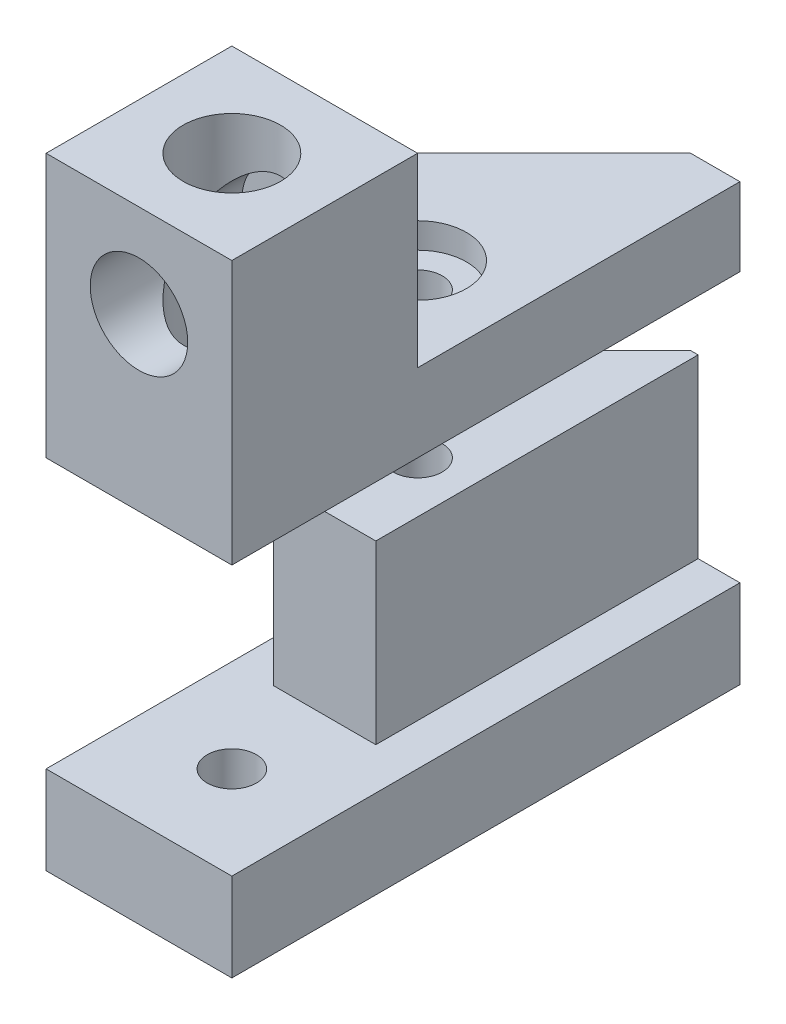
SolidWorks part; units mm, degrees
ref_plane "Front Plane" through (0, 0, 0) normal (0, 0, 1) x (1, 0, 0)
ref_plane "Top Plane" through (0, 0, 0) normal (0, 1, 0) x (1, 0, 0)
ref_plane "Right Plane" through (0, 0, 0) normal (1, 0, 0) x (0, 0, -1)
sketch "Sketch1" plane through (0, 0, 0) normal (0, 1, 0) x (1, 0, 0)
  line L1 (-10, 10) -> (10, 10) construction
  line L2 (-10, 10) -> (-10, -10) construction
  line L3 (-10, -10) -> (10, -10) construction
  line L4 (10, 10) -> (10, -10) construction
  line L5 (-10, 10) -> (10, -10) construction
  line L6 (-10, -10) -> (10, 10) construction
  line L7 (10, 10) -> (-10, 10) construction
  line L8 (10, 10) -> (10, 30) construction
  line L9 (10, 30) -> (-10, 30) construction
  line L10 (-10, 10) -> (-10, 30) construction
  circle A0 centre (0, 0) radius 2.5 construction
  circle A1 centre (0, 20) radius 2.5 construction
  circle A2 centre (0, 0) radius 6.5 construction
  circle A3 centre (0, 0) radius 7.5 construction
  circle A4 centre (0, 20) radius 2.5 construction
  circle A5 centre (0, 20) radius 7.5 construction
  circle A6 centre (0, 20) radius 6.5 construction
  point P0 (0, 0)
  point P6 (0, 0)
  point P10 (0, 20)
  dimension "D4" = 5
  dimension "D5" = 5
  dimension "D6" = 13
  dimension "D7" = 15
  dimension "D1" = 20
  dimension "D2" = 20
  dimension "D3" = 20
sketch "Sketch2" plane through (0, 0, 0) normal (0, 1, 0) x (1, 0, 0)
  line L1 (10, -10) -> (-10, -10)
  line L2 (10, -10) -> (10, 30)
  line L3 (10, 30) -> (-10, 30) construction
  line L4 (-10, -10) -> (-10, 30)
  line L5 (10, 44.7) -> (10, 30)
  line L6 (10, 30) -> (-10, 30) construction
  line L7 (-10, 30) -> (10, 30) construction
  line L9 (-10, 30) -> (10, 30) construction
  line L11 (10, 44.7) -> (4.7, 44.7)
  line L12 (-10, 30) -> (4.7, 44.7)
  line L13 (10.3961, 44.7) -> (10, 44.7) construction
  point P9 (0, 0)
  point P10 (9.6039, 42.7575)
  point P11 (0, 0)
  point P12 (0, 0)
  point P13 (-10, 42.5179)
  point P14 (3.8139, 42.3658)
  dimension "D1" = 14.7
  dimension "D2" = 5.3
extrude "idler bottom plate" add sketch "Sketch2" along normal blind 9.5
sketch "Sketch4" plane through (0, 9.5, 0) normal (0, 1, 0) x (1, 0, 0)
  line L0 (10, 30) -> (-10, 30) construction
  line L1 (-5.5, 30) -> (5.5, 30) construction
  line L2 (-5.5, 30) -> (-5.5, 10)
  line L3 (-5.5, 10) -> (5.5, 10)
  line L4 (5.5, 30) -> (5.5, 10)
  line L5 (-10, 10) -> (10, 10) construction
  line L12 (-5.5, 30) -> (-5.5, 34.5)
  line L13 (4.7, 44.7) -> (-10, 30) construction
  line L14 (-5.5, 34.5) -> (4.7, 44.7)
  line L15 (4.7, 44.7) -> (5.5, 44.7)
  line L16 (10, 44.7) -> (4.7, 44.7) construction
  line L17 (5.5, 44.7) -> (5.5, 30)
  circle A1 centre (0, 20) radius 6.5 construction
  point P8 (-6.5, 20)
  point P9 (6.5, 20)
  dimension "D1" = 1
  dimension "D2" = 1
extrude "connect wall" add sketch "Sketch4" along normal blind 19
sketch3d "top plate plane" plane through (0, 0, 0) normal (0, 0, 1) x (1, 0, 0)
  dimension "D1" = 10
sketch "Sketch5" plane through (0, 38.5, 0) normal (0, 1, 0) x (1, 0, 0)
  line L0 (-10, 30) -> (4.7, 44.7)
  line L1 (-10, 30) -> (10, 30) construction
  line L2 (-10, 30) -> (-10, -10)
  line L3 (-10, -10) -> (10, -10)
  line L4 (10, 30) -> (10, -10)
  line L7 (4.7, 44.7) -> (10, 44.7)
  line L8 (10, 44.7) -> (10, 30)
extrude "idler top plate" add sketch "Sketch5" along normal blind 8.4 separate body
sketch "Sketch6" plane through (0, 46.9, 0) normal (0, 1, 0) x (1, 0, 0)
  line L1 (-10, 10) -> (10, 10)
  line L2 (-10, 10) -> (-10, -10)
  line L3 (-10, -10) -> (10, -10)
  line L4 (10, 10) -> (10, -10)
extrude "2020 brace" add sketch "Sketch6" along normal blind 20
sketch "Sketch7" plane through (0, 66.9, 0) normal (0, 1, 0) x (1, 0, 0)
  circle A0 centre (0, 0) radius 5.25
  dimension "D1" = 10.5
extrude "Cut-Extrude1" cut sketch "Sketch7" against normal blind 20
sketch "Sketch8" plane through (0, 0, 10) normal (0, 0, 1) x (1, 0, 0)
  line L0 (-10, 66.9) -> (10, 66.9) construction
  line L1 (10, 66.9) -> (10, 38.5) construction
  circle A0 centre (0, 56.9) radius 5.25
  dimension "D1" = 10
  dimension "D3" = 10.5
  dimension "D2" = 10
extrude "Cut-Extrude2" cut sketch "Sketch8" against normal blind 13.6
sketch "Sketch15" plane through (0, 46.9, 0) normal (0, 1, 0) x (1, 0, 0)
  line L0 (-10, 10) -> (10, -10) construction
  point P0 (0, 20)
  point P1 (0, 0)
hole_wizard "CBORE for M5 SBHCS4" positions "Sketch15" profile "Sketch16" counterbore size "M5" standard "ANSI Metric" end condition through all
sketch "Sketch16" plane through (0, 46.9, -20) normal (1, 0, 0) x (0, 0, 1)
  line L0 (0, 0) -> (0, 46.9)
  line L1 (0, 46.9) -> (2.65, 46.9)
  line L3 (2.65, 46.9) -> (2.65, 2.75)
  line L4 (2.65, 2.75) -> (5.25, 2.75)
  line L5 (5.25, 2.75) -> (5.25, 0)
  line L7 (5.25, 0) -> (0, 0)
  line L11 (0, -6.35) -> (0, 107.95) construction
  dimension "Thru Hole Dia." = 5.3
  dimension "Thru Hole Depth" = 46.9
  dimension "C'Bore Dia." = 10.5
  dimension "C'Bore Depth" = 2.75
sketch "Sketch10" plane through (0, 0, -3.6) normal (0, 0, 1) x (1, 0, 0)
  circle A0 centre (0, 56.9) radius 5.5
  point P0 (0, 56.9)
hole_wizard "CBORE for M5 SBHCS2" positions "Sketch10" profile "Sketch11" counterbore size "M5" standard "ANSI Metric" end condition through all
sketch "Sketch11" plane through (0, 56.9, -3.6) normal (1, 0, 0) x (0, -1, 0)
  line L0 (0, 0) -> (0, 41.1)
  line L1 (0, 41.1) -> (2.65, 41.1)
  line L3 (2.65, 41.1) -> (2.65, 2.75)
  line L4 (2.65, 2.75) -> (5.25, 2.75)
  line L5 (5.25, 2.75) -> (5.25, 0)
  line L7 (5.25, 0) -> (0, 0)
  line L11 (0, -6.35) -> (0, 107.95) construction
  dimension "Thru Hole Dia." = 5.3
  dimension "Thru Hole Depth" = 41.1
  dimension "C'Bore Dia." = 10.5
  dimension "C'Bore Depth" = 2.75
fillet "Fillet1" [suppressed] radius 4
fillet "Fillet2" [suppressed] radius 1.5
fillet "Fillet4" [suppressed] radius 4
fillet "Fillet3" [suppressed] radius 1.5
fillet "Fillet5" [suppressed] radius 1.5
other "Save Bodies1"
equation "\"IDf695\"= 13mm"
equation "\"ODf695\"= 15mm"
equation "\"gt2Thickness\"= 1.38mm"
equation "\"m5Insert\"= 6.4mm"
